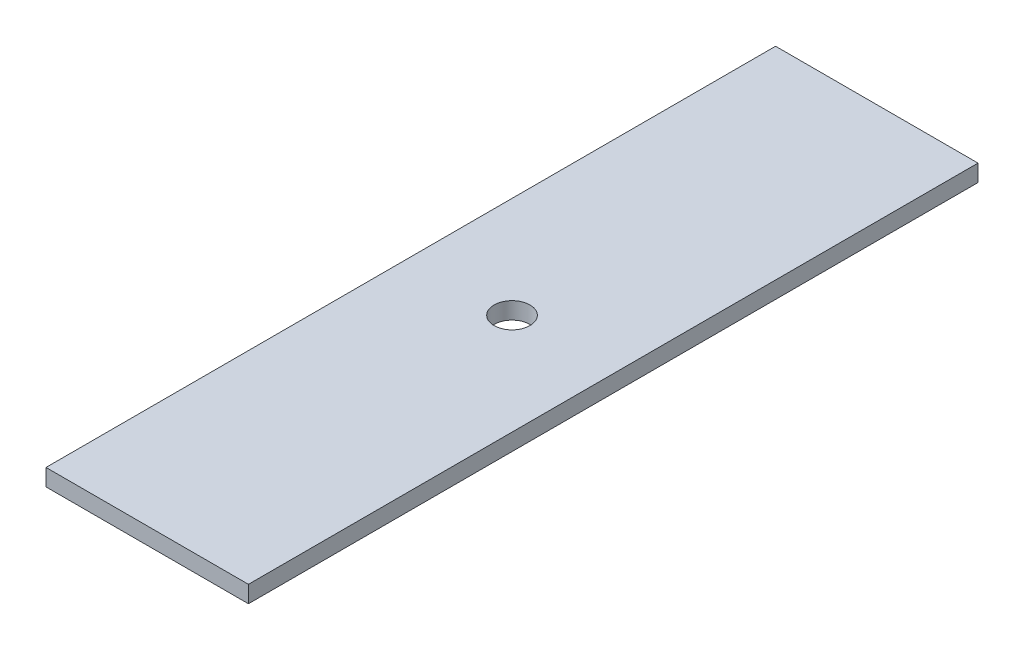
SolidWorks part; units mm, degrees
material "Alloy Steel"
ref_plane "Front Plane" through (0, 0, 0) normal (0, 0, 1) x (1, 0, 0)
ref_plane "Top Plane" through (0, 0, 0) normal (0, 1, 0) x (1, 0, 0)
ref_plane "Right Plane" through (0, 0, 0) normal (1, 0, 0) x (0, 0, -1)
sketch "Sketch1" plane through (0, 0, 0) normal (0, 1, 0) x (1, 0, 0)
  line L1 (38.1, -137.3188) -> (-38.1, -137.3188)
  line L2 (38.1, -137.3188) -> (38.1, 137.3187)
  line L3 (38.1, 137.3187) -> (-38.1, 137.3187)
  line L4 (-38.1, -137.3188) -> (-38.1, 137.3187)
  line L5 (38.1, -137.3188) -> (-38.1, 137.3187) construction
  line L6 (38.1, 137.3187) -> (-38.1, -137.3188) construction
  point P0 (0, 0)
  dimension "D1" = 76.2
  dimension "D2" = 274.6375
extrude "Boss-Extrude1" add sketch "Sketch1" along normal blind 6.35
sketch "Sketch2" plane through (0, 0, 0) normal (0, -1, 0) x (1, 0, 0)
  circle A1 centre (0, 0) radius 6.7462 construction
  circle A2 centre (0, 0) radius 6.7462
extrude "Cut-Extrude1" cut sketch "Sketch2" against normal through all
